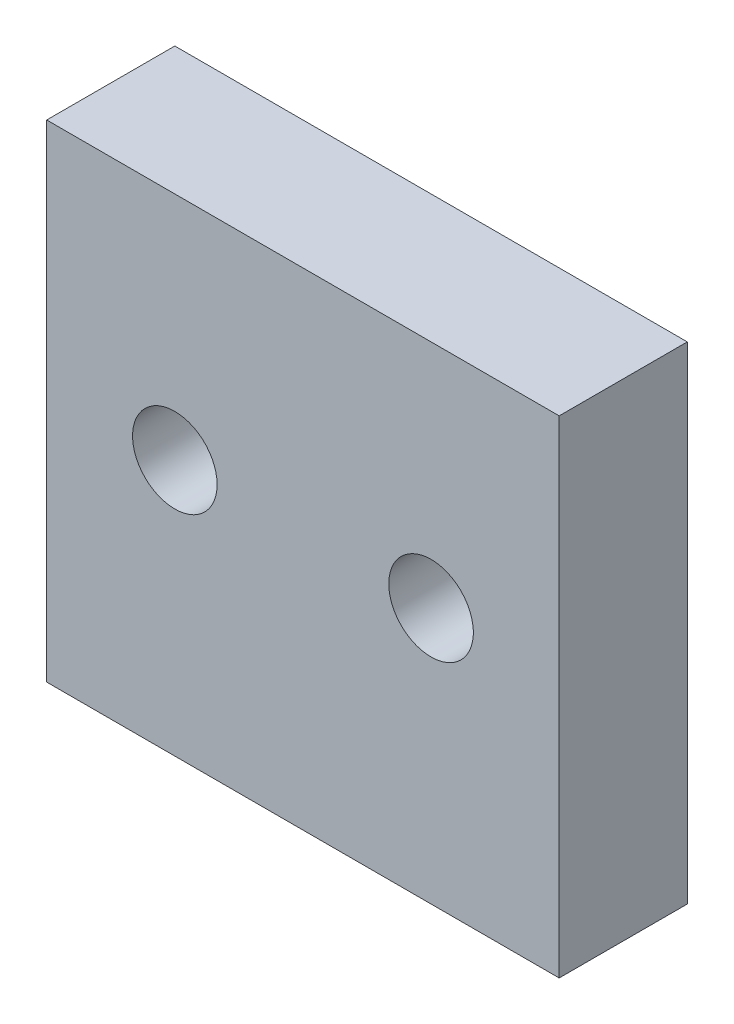
SolidWorks part; units mm, degrees
ref_plane "前视基准面" through (0, 0, 0) normal (0, 0, 1) x (1, 0, 0)
ref_plane "上视基准面" through (0, 0, 0) normal (0, 1, 0) x (1, 0, 0)
ref_plane "右视基准面" through (0, 0, 0) normal (1, 0, 0) x (0, 0, -1)
other "Configuration Table"
sketch "草图1" plane through (0, 0, 0) normal (0, 0, 1) x (1, 0, 0)
  line L0 (0, 0) -> (0, 13.4856) construction
  line L1 (-10, 10) -> (10, 10)
  line L2 (-10, 10) -> (-10, -10)
  line L3 (-10, -10) -> (10, -10)
  line L4 (10, 10) -> (10, -10)
  line L5 (-10, 10) -> (10, -10) construction
  line L6 (-10, -10) -> (10, 10) construction
  circle A0 centre (-5, 0) radius 1.65
  circle A1 centre (5, 0) radius 1.65
  point P0 (0, 0)
  point P12 (0, 0)
  dimension "D3" = 3.3
  dimension "D4" = 10
  dimension "D1" = 20
  dimension "D2" = 20
extrude "凸台-拉伸1" add sketch "草图1" along normal blind 5
sketch "草图2" plane through (0, 0, 5) normal (0, 0, 1) x (1, 0, 0)
  line L0 (10, -10) -> (10, 10) construction
  line L1 (-10, 10) -> (10, 10)
  line L2 (-10, 10) -> (-10, 9)
  line L3 (-10, 9) -> (10, 9)
  line L4 (10, 10) -> (10, 9)
  dimension "D1" = 1
extrude "切除-拉伸1" cut sketch "草图2" against normal blind 5
